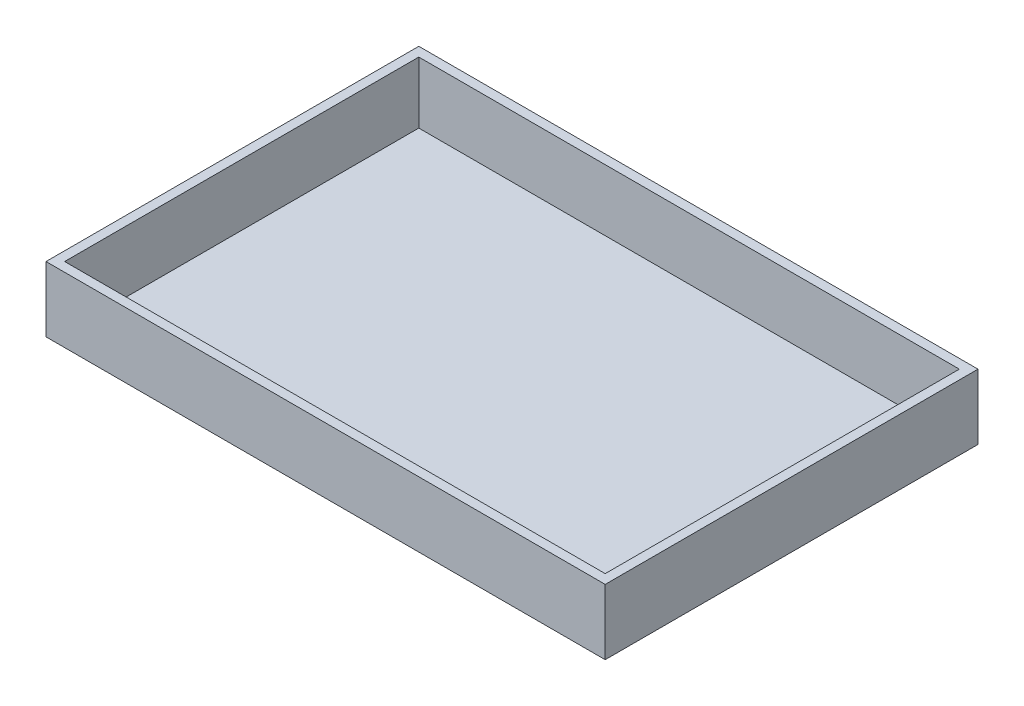
SolidWorks part; units mm, degrees
ref_plane "Front Plane" through (0, 0, 0) normal (0, 0, 1) x (1, 0, 0)
ref_plane "Top Plane" through (0, 0, 0) normal (0, 1, 0) x (1, 0, 0)
ref_plane "Right Plane" through (0, 0, 0) normal (1, 0, 0) x (0, 0, -1)
sketch "Sketch1" plane through (0, 0, 0) normal (0, 0, 1) x (1, 0, 0)
  line L1 (15, -1.75) -> (-15, -1.75)
  line L2 (15, -1.75) -> (15, 1.75)
  line L3 (15, 1.75) -> (-15, 1.75)
  line L4 (-15, -1.75) -> (-15, 1.75)
  line L5 (15, -1.75) -> (-15, 1.75) construction
  line L6 (15, 1.75) -> (-15, -1.75) construction
  point P0 (0, 0)
  dimension "D1" = 30
  dimension "D2" = 3.5
extrude "Boss-Extrude1" add sketch "Sketch1" along normal blind 20
sketch "Sketch2" plane through (0, 1.75, 0) normal (0, 1, 0) x (1, 0, 0)
  line L0 (15, -20) -> (15, 0) construction
  line L1 (14.5, -19.5) -> (-14.5, -19.5)
  line L2 (14.5, -19.5) -> (14.5, -0.5)
  line L3 (14.5, -0.5) -> (-14.5, -0.5)
  line L4 (-14.5, -19.5) -> (-14.5, -0.5)
  line L5 (14.5, -19.5) -> (-14.5, -0.5) construction
  line L6 (14.5, -0.5) -> (-14.5, -19.5) construction
  line L7 (15, -20) -> (-15, -20) construction
  point P0 (0, -10)
  dimension "D1" = 29
  dimension "D2" = 15
  dimension "D3" = 10
  dimension "D4" = 19
extrude "Cut-Extrude1" cut sketch "Sketch2" against normal blind 3.3
